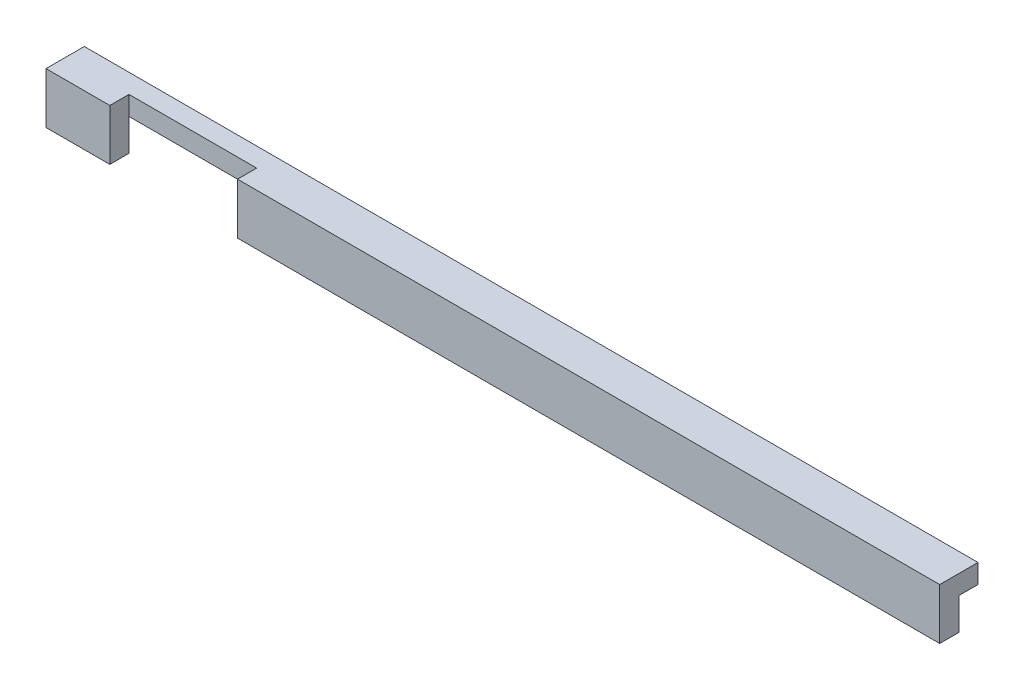
SolidWorks part; units mm, degrees
ref_plane "Front Plane" through (0, 0, 0) normal (0, 0, 1) x (1, 0, 0)
ref_plane "Top Plane" through (0, 0, 0) normal (0, 1, 0) x (1, 0, 0)
ref_plane "Right Plane" through (0, 0, 0) normal (1, 0, 0) x (0, 0, -1)
sketch "Sketch1" plane through (0, 0, 0) normal (0, 1, 0) x (1, 0, 0)
  line L1 (70, -4) -> (-70, -4)
  line L2 (70, -4) -> (70, 4)
  line L3 (70, 4) -> (-70, 4)
  line L4 (-70, -4) -> (-70, 4)
  line L5 (70, -4) -> (-70, 4) construction
  line L6 (70, 4) -> (-70, -4) construction
  point P0 (0, 0)
  dimension "D1" = 140
  dimension "D2" = 8
extrude "Boss-Extrude1" add sketch "Sketch1" along normal blind 8
ref_plane "Plane1" through (70, 0, 0) normal (1, 0, 0) x (0, 0, -1)
sketch "Sketch2" plane through (70, 0, 0) normal (1, 0, 0) x (0, 0, -1)
  line L0 (-4, 8) -> (4, 8) construction
  line L1 (4, 0) -> (1, 0)
  line L2 (4, 0) -> (4, 5)
  line L3 (4, 5) -> (1, 5)
  line L4 (1, 0) -> (1, 5)
  line L5 (-4, 0) -> (-2, 0)
  line L6 (-4, 0) -> (-4, 8)
  line L7 (-4, 8) -> (-2, 8)
  line L8 (-2, 0) -> (-2, 8)
  dimension "D1" = 3
  dimension "D2" = 5
  dimension "D3" = 2
extrude "Cut-Extrude1" cut sketch "Sketch2" against normal blind 140
ref_plane "Plane2" through (0, 0, 2) normal (0, 0, 1) x (1, 0, 0)
sketch "Sketch3" plane through (0, 0, 2) normal (0, 0, 1) x (1, 0, 0)
  line L0 (-70, 4) -> (-60, 4) construction
  line L1 (-70, 0) -> (-70, 8) construction
  line L2 (-60, 4) -> (-60, 8) construction
  line L3 (-70, 8) -> (70, 8) construction
  line L4 (-70, 0) -> (70, 0) construction
  line L5 (-60, 8) -> (-40, 8)
  line L6 (-60, 8) -> (-60, 0)
  line L7 (-60, 0) -> (-40, 0)
  line L8 (-40, 8) -> (-40, 0)
  dimension "D1" = 10
  dimension "D2" = 20
extrude "Cut-Extrude2" cut sketch "Sketch3" against normal blind 3
